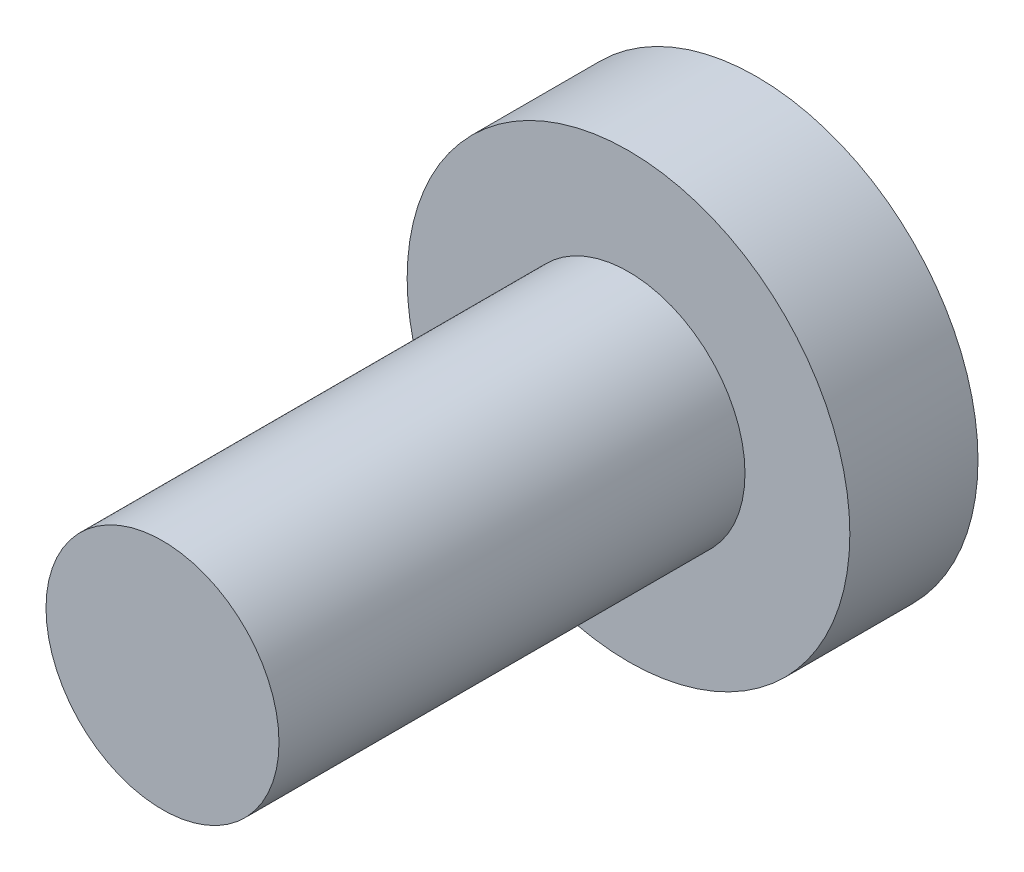
SolidWorks part; units mm, degrees
ref_plane "Front Plane" through (0, 0, 0) normal (0, 0, 1) x (1, 0, 0)
ref_plane "Top Plane" through (0, 0, 0) normal (0, 1, 0) x (1, 0, 0)
ref_plane "Right Plane" through (0, 0, 0) normal (1, 0, 0) x (0, 0, -1)
sketch "S01 - ISO 7380 button head clearance envelope" plane through (0, 0, 0) normal (0, 0, 1) x (1, 0, 0)
  circle A0 centre (0, 0) radius 2.85
  dimension "D1" = 5.7
extrude "01 - ISO 7380 button head clearance envelope" add sketch "S01 - ISO 7380 button head clearance envelope" along normal blind 1.65 from offset 1.65
sketch "S02 - M3 underhead length" plane through (0, 0, 0) normal (0, 0, 1) x (1, 0, 0)
  circle A0 centre (0, 0) radius 1.5
  dimension "D1" = 3
extrude "02 - M3 underhead length" add sketch "S02 - M3 underhead length" along normal blind 6
sketch "S03 - Button head hex socket" plane through (0, 0, 0) normal (0, 0, 1) x (1, 0, 0)
  line L0 (1.1547, 0) -> (0.5774, 1)
  line L1 (0.5774, 1) -> (-0.5774, 1)
  line L2 (-0.5774, 1) -> (-1.1547, 0)
  line L3 (-1.1547, 0) -> (-0.5774, -1)
  line L4 (-0.5774, -1) -> (0.5774, -1)
  line L5 (0.5774, -1) -> (1.1547, 0)
  dimension "D1" = 0.5774
  dimension "D2" = 1.1547
  dimension "D3" = 0.5774
  dimension "D4" = 1.1547
  dimension "D5" = 1
  dimension "D6" = 1
extrude "03 - Button head hex socket" cut sketch "S03 - Button head hex socket" along normal blind 1.12 from offset 1.75
